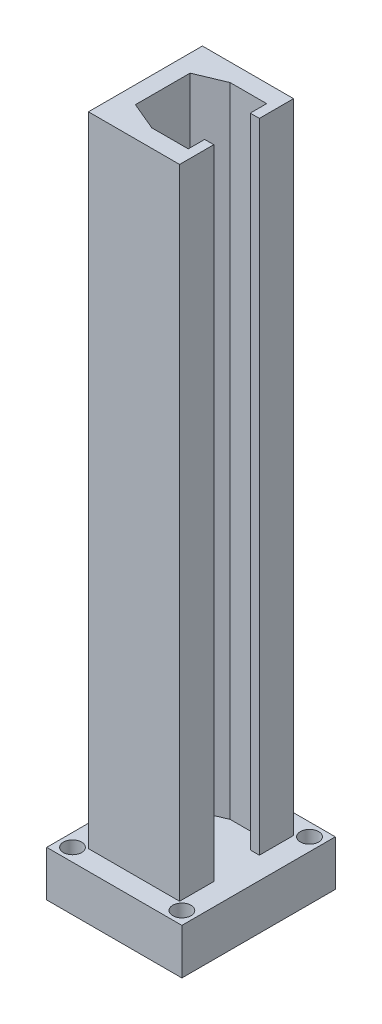
SolidWorks part; units mm, degrees
ref_plane "Front Plane" through (0, 0, 0) normal (0, 0, 1) x (1, 0, 0)
ref_plane "Top Plane" through (0, 0, 0) normal (0, 1, 0) x (1, 0, 0)
ref_plane "Right Plane" through (0, 0, 0) normal (1, 0, 0) x (0, 0, -1)
sketch "Sketch1" plane through (0, 0, 0) normal (0, 1, 0) x (1, 0, 0)
  line L1 (-10, -12.5) -> (10, -12.5)
  line L2 (-10, -12.5) -> (-10, 12.5)
  line L3 (-10, 12.5) -> (10, 12.5)
  line L4 (10, -12.5) -> (10, 12.5)
  line L7 (10, 0) -> (10, 5)
  line L8 (10, 5) -> (10, -5)
  line L9 (10, -5) -> (8, -5)
  line L11 (8, 5) -> (10, 5)
  line L13 (0, 8.6) -> (8, 8.6)
  line L14 (8, 8.6) -> (8, 5)
  line L16 (0, -8.6) -> (8, -8.6)
  line L17 (8, -8.6) -> (8, -5)
  line L18 (8, 8.6) -> (0, 8.6)
  line L22 (-6.2, 0) -> (-6.2, 6)
  line L23 (-6.2, 6) -> (-6.2, -6)
  line L24 (-6.2, -6) -> (0, -8.6)
  line L25 (0, 8.6) -> (-6.2, 6)
  line L27 (-6.2, 6) -> (-6.2, -6)
  point P0 (0, 0)
extrude "Boss-Extrude2" add sketch "Sketch1" along normal blind 150 contours L25 L13 L14 L11 L4 L3 L2 L1 L9 L17 L16 L24 L23 L22
sketch "Sketch3" plane through (0, 0, 0) normal (0, 1, 0) x (1, 0, 0)
  line L7 (14.8284, -16.8284) -> (14.8284, 16.8284)
  line L9 (-14.8284, -16.8284) -> (-14.8284, 16.8284)
  line L11 (14.8284, 16.8284) -> (-14.8284, 16.8284)
  line L13 (14.8284, -16.8284) -> (-14.8284, -16.8284)
  circle A0 centre (-12, 14) radius 2
  circle A1 centre (-12, -14) radius 2
  circle A2 centre (12, 14) radius 2
  circle A3 centre (12, -14) radius 2
extrude "Boss-Extrude3" add sketch "Sketch3" along normal blind 10
